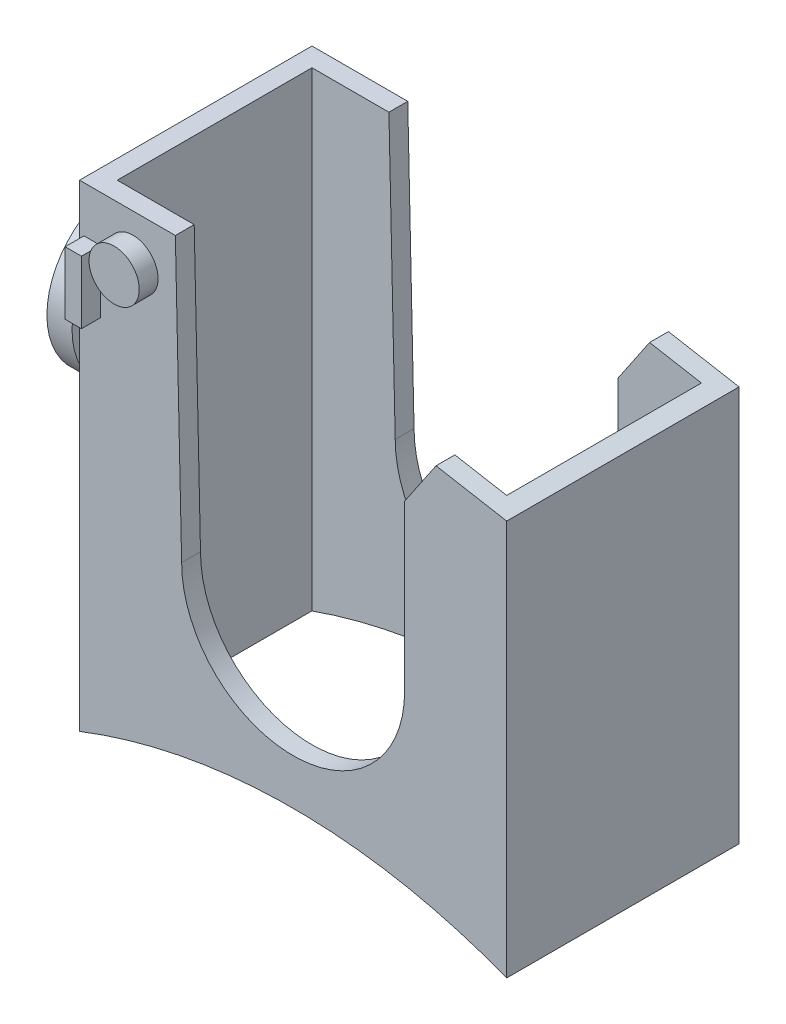
SolidWorks part; units mm, degrees
ref_plane "Alzado" through (0, 0, 0) normal (0, 0, 1) x (1, 0, 0)
ref_plane "Planta" through (0, 0, 0) normal (0, 1, 0) x (1, 0, 0)
ref_plane "Vista lateral" through (0, 0, 0) normal (1, 0, 0) x (0, 0, -1)
sketch "Croquis1" plane through (0, 0, 0) normal (0, 0, 1) x (1, 0, 0)
  line L0 (-34, 44.6) -> (-34, -31.4)
  line L1 (0, -25) -> (41.8445, -25) construction
  line L2 (34, -31.4) -> (34, 31.6)
  line L3 (-34, 44.6) -> (-18.75, 44.6)
  line L4 (-18.75, 44.6) -> (-17.75, 0)
  line L5 (17.75, 0) -> (17.75, 26.2154)
  line L6 (17.75, 26.2154) -> (22.75, 33.6)
  line L7 (0, 36.42) -> (0, -73.9155) construction
  line L8 (22.75, 33.6) -> (34, 31.6)
  arc A0 (-17.75, 0) -> (17.75, 0) centre (0, 0) ccw
  arc A1 (-34, -31.4) -> (34, -31.4) centre (0, -118.5125) cw
  dimension "D1" = 35.5
  dimension "D2" = 68
  dimension "D3" = 25
  dimension "D4" = 6.4
  dimension "D5" = 76
  dimension "D6" = 63
  dimension "D7" = 65
  dimension "D8" = 5
  dimension "D9" = 15.25
extrude "Saliente-Extruir1" add sketch "Croquis1" along normal mid plane 37
sketch "Croquis2" plane through (0, 0, 0) normal (0, 1, 0) x (1, 0, 0)
  line L0 (-34, -18.5) -> (-34, 18.5) construction
  line L1 (-17.75, -18.5) -> (-18.75, -18.5) construction
  line L2 (-18.75, -18.5) -> (-34, -18.5) construction
  line L3 (-17.75, -18.5) -> (17.75, -18.5) construction
  line L4 (22.75, -18.5) -> (17.75, -18.5) construction
  line L5 (34, -18.5) -> (22.75, -18.5) construction
  line L6 (34, -18.5) -> (34, 18.5) construction
  line L7 (34, 18.5) -> (22.75, 18.5) construction
  line L8 (22.75, 18.5) -> (17.75, 18.5) construction
  line L9 (17.75, 18.5) -> (-17.75, 18.5) construction
  line L10 (-17.75, 18.5) -> (-18.75, 18.5) construction
  line L11 (-18.75, 18.5) -> (-34, 18.5) construction
  line L12 (-34, -18.5) -> (-34, 18.5)
  line L13 (-17.75, -18.5) -> (-18.75, -18.5)
  line L14 (-18.75, -18.5) -> (-34, -18.5)
  line L15 (-17.75, -18.5) -> (17.75, -18.5)
  line L16 (22.75, -18.5) -> (17.75, -18.5)
  line L17 (34, -18.5) -> (22.75, -18.5)
  line L18 (34, -18.5) -> (34, 18.5)
  line L19 (34, 18.5) -> (22.75, 18.5)
  line L20 (22.75, 18.5) -> (17.75, 18.5)
  line L21 (17.75, 18.5) -> (-17.75, 18.5)
  line L22 (-17.75, 18.5) -> (-18.75, 18.5)
  line L23 (-18.75, 18.5) -> (-34, 18.5)
  line L28 (-31, -15.5) -> (-31, 15.5)
  line L29 (-18.75, 15.5) -> (-31, 15.5)
  line L30 (-17.75, 15.5) -> (-18.75, 15.5)
  line L31 (17.75, 15.5) -> (-17.75, 15.5)
  line L32 (22.75, 15.5) -> (17.75, 15.5)
  line L33 (31, 15.5) -> (22.75, 15.5)
  line L34 (31, -15.5) -> (31, 15.5)
  line L35 (31, -15.5) -> (22.75, -15.5)
  line L36 (22.75, -15.5) -> (17.75, -15.5)
  line L37 (-17.75, -15.5) -> (17.75, -15.5)
  line L38 (-17.75, -15.5) -> (-18.75, -15.5)
  line L39 (-18.75, -15.5) -> (-31, -15.5)
  dimension "D1" = 3
extrude "Cortar-Extruir1" cut sketch "Croquis2" against normal mid plane 107 contours L39 L38 L37 L36 L35 L34 L33 L32 L31 L30 L29 L28
sketch "Croquis3" plane through (0, 0, 0) normal (0, 0, 1) x (1, 0, 0)
  line L0 (0, -4.4224) -> (0, 45.7431) construction
  line L1 (19.4782, 17.6) -> (-50.6345, 17.6) construction
  line L2 (-34, 17.6) -> (-34, 3.6)
  line L3 (-34, 3.6) -> (-37, 3.6)
  line L4 (-37, 3.6) -> (-37, 10.3)
  line L5 (-37, 10.3) -> (-41, 10.3)
  line L6 (-41, 10.3) -> (-41, 4.9)
  line L7 (-41, 4.9) -> (-45, 4.9)
  line L8 (-45, 4.9) -> (-45, 17.6)
  line L9 (-45, 17.6) -> (-34, 17.6)
  line L10 (-34, 44.6) -> (-34, -31.4) construction
  dimension "D1" = 3
  dimension "D2" = 4
  dimension "D3" = 5.4
  dimension "D4" = 12.7
  dimension "D5" = 14
  dimension "D6" = 35
  dimension "D7" = 4
revolve "Revolución1" add sketch "Croquis3" angle 360 about L1
sketch "Croquis4" plane through (0, 0, 18.5) normal (0, 0, 1) x (1, 0, 0)
  line L0 (0, 79.9688) -> (0, -55.486) construction
  line L1 (73.0329, 37.27) -> (-80.2548, 37.27) construction
  line L2 (-34, 44.6) -> (-34, -31.4) construction
  line L3 (-33.3, 37.27) -> (-30.7, 37.27)
  line L4 (-33.3, 37.27) -> (-33.3, 27.27)
  line L5 (-33.3, 27.27) -> (-30.7, 27.27)
  line L6 (-30.7, 37.27) -> (-30.7, 27.27)
  line L8 (-18.75, 44.6) -> (-34, 44.6) construction
  circle A0 centre (-25.5, 37.27) radius 4
  dimension "D5" = 8
  dimension "D6" = 5.2
  dimension "D1" = 8.5
  dimension "D2" = 7.33
  dimension "D3" = 2.6
  dimension "D4" = 10
extrude "Saliente-Extruir3" add sketch "Croquis4" along normal blind 3
